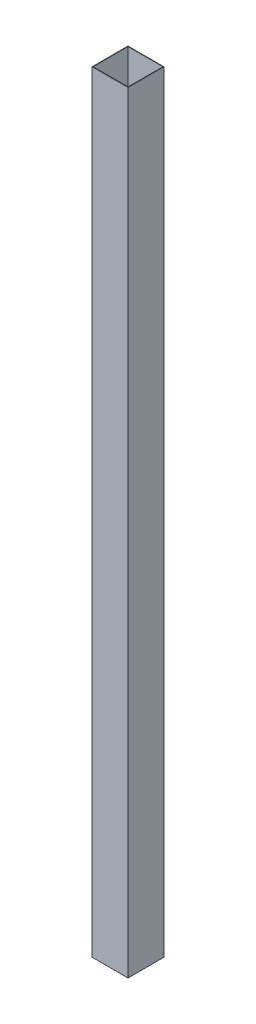
SolidWorks part; units mm, degrees
ref_plane "Front Plane" through (0, 0, 0) normal (0, 0, 1) x (1, 0, 0)
ref_plane "Top Plane" through (0, 0, 0) normal (0, 1, 0) x (1, 0, 0)
ref_plane "Right Plane" through (0, 0, 0) normal (1, 0, 0) x (0, 0, -1)
sketch "Sketch1" plane through (0, 0, 0) normal (0, 1, 0) x (1, 0, 0)
  line L1 (-20, -20) -> (20, -20)
  line L2 (-20, -20) -> (-20, 20)
  line L3 (-20, 20) -> (20, 20)
  line L4 (20, -20) -> (20, 20)
  line L5 (-20, -20) -> (20, 20) construction
  line L6 (-20, 20) -> (20, -20) construction
  point P0 (0, 0)
  dimension "D1" = 40
  dimension "D2" = 40
extrude "Boss-Extrude2" add sketch "Sketch1" along normal blind 860
sketch "Sketch2" plane through (0, 0, 0) normal (0, -1, 0) x (1, 0, 0)
  line L1 (-19.5, -19.5) -> (19.5, -19.5)
  line L2 (-19.5, -19.5) -> (-19.5, 19.5)
  line L3 (-19.5, 19.5) -> (19.5, 19.5)
  line L4 (19.5, -19.5) -> (19.5, 19.5)
  line L5 (-19.5, -19.5) -> (19.5, 19.5) construction
  line L6 (-19.5, 19.5) -> (19.5, -19.5) construction
  point P0 (0, 0)
  dimension "D1" = 39
  dimension "D2" = 39
extrude "Cut-Extrude1" cut sketch "Sketch2" against normal through all
